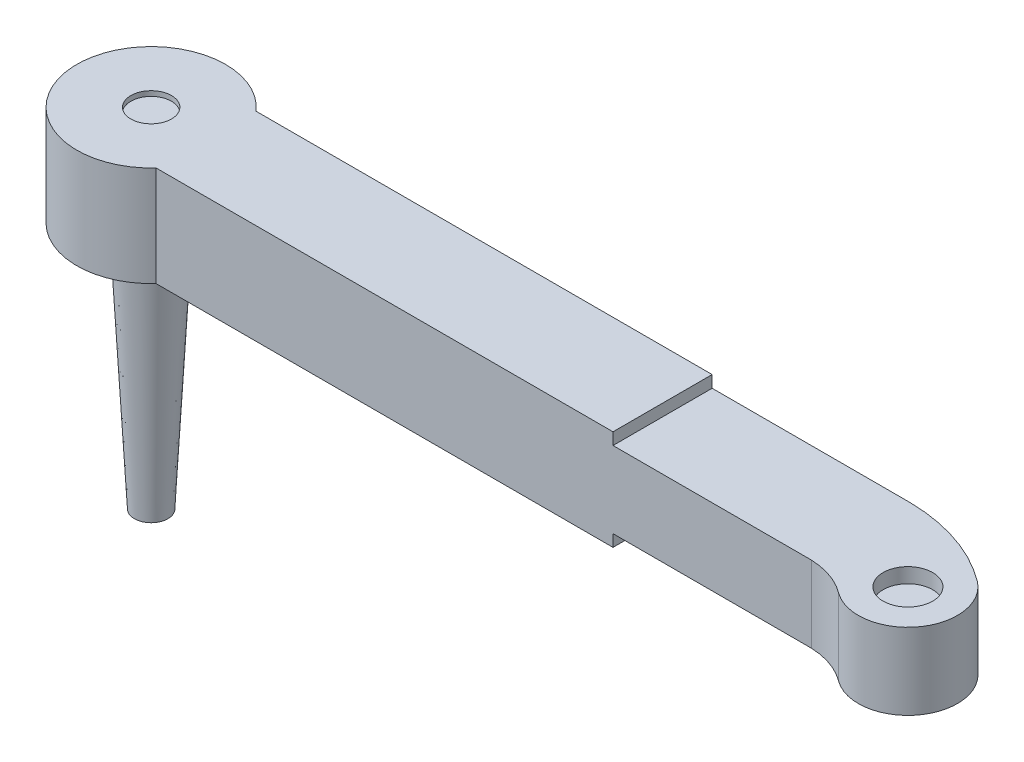
SolidWorks part; units mm, degrees
ref_plane "Alzado" through (0, 0, 0) normal (0, 0, 1) x (1, 0, 0)
ref_plane "Planta" through (0, 0, 0) normal (0, 1, 0) x (1, 0, 0)
ref_plane "Vista lateral" through (0, 0, 0) normal (1, 0, 0) x (0, 0, -1)
sketch "Croquis1" plane through (0, 0, 0) normal (0, 1, 0) x (1, 0, 0)
  line L1 (-33.0719, -5.0036) -> (33.0239, -5.0036)
  line L3 (-32.9761, 4.9964) -> (33.0239, 4.9964)
  line L4 (33.0239, -5.0036) -> (33.0239, 4.9964)
  line L5 (-33.0719, -5.0036) -> (33.0239, 4.9964) construction
  line L6 (-32.9761, 4.9964) -> (33.0239, -5.0036) construction
  arc A0 (-32.9761, 4.9964) -> (-33.0719, -5.0036) centre (-38.6137, 0.0499) ccw
  point P0 (0, 0)
  dimension "D3" = 15
  dimension "D1" = 10
  dimension "D2" = 66
extrude "Saliente-Extruir1" add sketch "Croquis1" along normal blind 10.1
sketch "Croquis7" plane through (0, 10.1, 0) normal (0, 1, 0) x (1, 0, 0)
  circle A0 centre (-38.6137, 0.0499) radius 2.05
  dimension "D1" = 4.1
extrude "Cortar-Extruir1" cut sketch "Croquis7" against normal blind 0.5
sketch "Croquis11" plane through (0, 0, 5.0036) normal (0, 0, 1) x (1, 0, 0)
  line L0 (-33.0719, 10.1) -> (33.0239, 10.1) construction
  line L1 (13.0239, 10.1) -> (33.0239, 10.1)
  line L2 (13.0239, 10.1) -> (13.0239, 8.9)
  line L3 (13.0239, 8.9) -> (33.0239, 8.9)
  line L4 (33.0239, 10.1) -> (33.0239, 8.9)
  line L5 (33.0239, 10.1) -> (33.0239, 0) construction
  line L6 (-33.0719, 0) -> (33.0239, 0) construction
  line L7 (13.0239, 0) -> (33.0239, 0)
  line L8 (13.0239, 0) -> (13.0239, 1.2)
  line L9 (13.0239, 1.2) -> (33.0239, 1.2)
  line L10 (33.0239, 0) -> (33.0239, 1.2)
  dimension "D1" = 20
  dimension "D2" = 1.2
  dimension "D3" = 0
  dimension "D4" = 0
extrude "Cortar-Extruir4" cut sketch "Croquis11" against normal through all
ref_plane "Plano1" through (0, 5.05, 0) normal (0, 1, 0) x (1, 0, 0)
sketch "Croquis12" plane through (0, 8.9, 0) normal (0, 1, 0) x (1, 0, 0)
  line L0 (33.0239, 4.9964) -> (33.0239, -5.0036) construction
  line L1 (33.0239, 4.9964) -> (33.0239, -5.0036)
  arc A0 (33.0239, -0.0036) -> (40.2399, -2.476) centre (32.7732, -12.5018) cw construction
  arc A1 (43.3062, 1.4734) -> (33.0239, 4.9964) centre (32.7732, -12.5018) ccw
  arc A2 (37.3344, -6.5452) -> (33.0239, -5.0036) centre (32.7732, -12.5018) ccw
  arc A3 (37.3344, -6.5452) -> (43.3062, 1.4734) centre (40.2399, -2.476) ccw
  point P3 (34.0582, -1.4684)
  dimension "D1" = 5
  dimension "D2" = 17.5
extrude "Saliente-Extruir4" add sketch "Croquis12" against normal up to vertex
sketch "Croquis13" plane through (0, 8.9, 0) normal (0, 1, 0) x (1, 0, 0)
  circle A0 centre (40.2399, -2.476) radius 2.5
  dimension "D1" = 5
extrude "Cortar-Extruir5" cut sketch "Croquis13" against normal blind 1.5
sketch "Croquis14" plane through (0, 0, 0) normal (0, -1, 0) x (1, 0, 0)
  circle A0 centre (-38.6137, -0.0499) radius 3
  dimension "D1" = 6
extrude "Saliente-Extruir5" add sketch "Croquis14" along normal blind 25 draft 3
mirror "Simetría1" about plane through (0, 5.05, 0) normal (0, 1, 0) of "Cortar-Extruir5"
